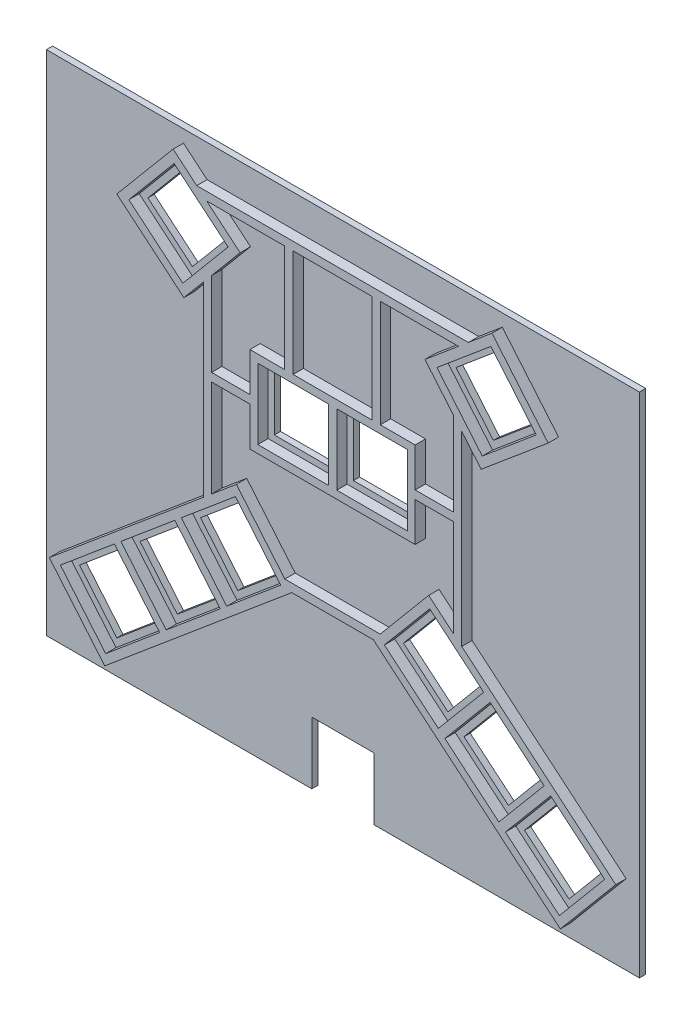
SolidWorks part; units mm, degrees
ref_plane "Alzado" through (0, 0, 0) normal (0, 0, 1) x (1, 0, 0)
ref_plane "Planta" through (0, 0, 0) normal (0, 1, 0) x (1, 0, 0)
ref_plane "Vista lateral" through (0, 0, 0) normal (1, 0, 0) x (0, 0, -1)
sketch "Model" plane through (0, 0, 0) normal (0, 0, 1) x (1, 0, 0)
  line L0 (0, 114.3975) -> (135.05, 114.3975)
  line L1 (135.05, 114.3975) -> (135.05, 0)
  line L2 (135.05, 0) -> (0, 0)
  line L3 (0, 0) -> (0, 114.3975)
  line L4 (51, 35) -> (65, 35)
  line L5 (65, 35) -> (65, 49)
  line L6 (65, 49) -> (51, 49)
  line L7 (51, 49) -> (51, 35)
  line L8 (67.525, 0) -> (67.525, 114.3975) construction
  line L9 (18.5931, 87.4278) -> (29.3178, 78.4288)
  line L10 (29.3178, 78.4288) -> (38.3168, 89.1534)
  line L11 (38.3168, 89.1534) -> (27.5922, 98.1524)
  line L12 (103.8144, 23.7236) -> (114.539, 14.7246)
  line L13 (94.8154, 12.999) -> (103.8144, 23.7236)
  line L14 (105.54, 4) -> (94.8154, 12.999)
  line L15 (114.539, 14.7246) -> (105.54, 4)
  line L16 (27.5922, 98.1524) -> (18.5931, 87.4278)
  line L17 (33.1863, 75.1827) -> (43.9109, 66.1836)
  line L18 (43.9109, 66.1836) -> (52.9099, 76.9083)
  line L19 (52.9099, 76.9083) -> (42.1853, 85.9073)
  line L20 (42.1853, 85.9073) -> (33.1863, 75.1827)
  line L21 (20.511, 14.7246) -> (29.51, 4)
  line L22 (29.51, 4) -> (40.2346, 12.999)
  line L23 (40.2346, 12.999) -> (31.2356, 23.7236)
  line L24 (31.2356, 23.7236) -> (20.511, 14.7246)
  line L25 (84.05, 49) -> (84.05, 35)
  line L26 (70.05, 49) -> (84.05, 49)
  line L27 (70.05, 35) -> (70.05, 49)
  line L28 (84.05, 35) -> (70.05, 35)
  line L29 (92.8647, 85.9073) -> (101.8637, 75.1827)
  line L30 (82.1401, 76.9083) -> (92.8647, 85.9073)
  line L31 (91.1391, 66.1836) -> (82.1401, 76.9083)
  line L32 (101.8637, 75.1827) -> (91.1391, 66.1836)
  line L33 (107.4578, 98.1524) -> (116.4569, 87.4278)
  line L34 (96.7332, 89.1534) -> (107.4578, 98.1524)
  line L35 (105.7322, 78.4288) -> (96.7332, 89.1534)
  line L36 (4, 99.6729) -> (14.7246, 90.6739)
  line L37 (14.7246, 90.6739) -> (23.7236, 101.3985)
  line L38 (23.7236, 101.3985) -> (12.999, 110.3975)
  line L39 (12.999, 110.3975) -> (4, 99.6729)
  line L40 (116.4569, 87.4278) -> (105.7322, 78.4288)
  line L41 (120.3254, 90.6739) -> (111.3264, 101.3985)
  line L42 (131.05, 99.6729) -> (120.3254, 90.6739)
  line L43 (122.051, 110.3975) -> (131.05, 99.6729)
  line L44 (4, 99.6729) -> (0, 99.6729) construction
  line L45 (111.3264, 101.3985) -> (122.051, 110.3975)
  line L46 (27.5922, 98.1524) -> (29.3178, 78.4288) construction
  line L47 (107.4578, 98.1524) -> (105.7322, 78.4288) construction
  line L48 (51, 35) -> (65, 49) construction
  line L49 (70.05, 49) -> (84.05, 35) construction
  line L50 (20.511, 14.7246) -> (40.2346, 12.999) construction
  line L51 (4, 99.6729) -> (0, 103.0293) construction
  line L52 (103.8144, 23.7236) -> (105.54, 4) construction
  line L54 (-4, 118.3975) -> (139.05, 118.3975)
  line L55 (-4, 118.3975) -> (-4, -4)
  line L56 (-4, -4) -> (139.05, -4)
  line L57 (139.05, 118.3975) -> (139.05, -4)
  line L58 (-4, 118.3975) -> (139.05, -4) construction
  line L59 (-4, -4) -> (139.05, 118.3975) construction
  point P8 (28.455, 88.2906)
  point P23 (106.595, 88.2906)
  point P50 (58, 42)
  point P51 (77.05, 42)
  point P52 (30.3728, 13.8618)
  point P54 (104.6772, 13.8618)
  point P55 (67.525, 57.1988)
  dimension "D1" = 14
  dimension "D8" = 4
  dimension "D2" = 4
  dimension "D3" = 40
  dimension "D4" = 114.3975
  dimension "D5" = 5.05
  dimension "D9" = 5.05
  dimension "D10" = 50
  dimension "D6" = 4
  dimension "D11" = 29.51
  dimension "D7" = 35
  dimension "D12" = 51
  dimension "D13" = 5.05
  dimension "D14" = 135.05
  dimension "D15" = 28.455
  dimension "D16" = 26.1069
  dimension "D17" = 106.595
  dimension "D18" = 26.1069
  dimension "D19" = 19.05
  dimension "D20" = 72.3975
  dimension "D21" = 67.525
  dimension "D22" = 100.5357
  dimension "D23" = 30.3728
  dimension "D24" = 104.6772
  dimension "D25" = 4
  dimension "D26" = 4
extrude "Saliente-Extruir1" add sketch "Model" along normal mid plane 1.5 contours L3 L2 L1 L0 L39 L38 L37 L36 L24 L23 L22 L21 L20 L19 L18 L17 L16 L11 L10 L9 L7 L6 L5 L4 L12 L15 L14 L13 L25 L28 L27 L26 L29 L32 L31 L30 L33 L40 L35 L34 L41 | L57 L54 L55 L56 L2 L3 L0 L1
sketch "Croquis1" plane through (0, 0, 0.75) normal (0, 0, 1) x (1, 0, 0)
  line L0 (-4, 118.3975) -> (-4, -4) construction
  line L2 (-4, 118.3975) -> (139.05, 118.3975) construction
  point P0 (12.5, 80.9213)
  dimension "D1" = 16.5
  dimension "D3" = 37.4762
sketch "Croquis2" plane through (0, 0, 0.75) normal (0, 0, 1) x (1, 0, 0)
  line L0 (-4, 118.3975) -> (139.05, 118.3975) construction
  line L1 (60.025, 133.3975) -> (75.025, 133.3975)
  line L2 (60.025, 133.3975) -> (60.025, 103.3975)
  line L3 (60.025, 103.3975) -> (75.025, 103.3975)
  line L4 (75.025, 133.3975) -> (75.025, 103.3975)
  line L5 (60.025, 133.3975) -> (75.025, 103.3975) construction
  line L6 (60.025, 103.3975) -> (75.025, 133.3975) construction
  point P0 (67.525, 118.3975)
  dimension "D1" = 15
  dimension "D2" = 15
extrude "Cortar-Extruir1" cut sketch "Croquis2" against normal through all
sketch "Croquis5" plane through (0, 0, -0.75) normal (0, 0, -1) x (-1, 0, 0)
  line L4 (-120.3254, 90.6739) -> (-111.3264, 101.3985)
  line L5 (-131.05, 99.6729) -> (-120.3254, 90.6739)
  line L6 (-122.051, 110.3975) -> (-131.05, 99.6729)
  line L7 (-111.3264, 101.3985) -> (-122.051, 110.3975)
  line L8 (-120.3254, 90.6739) -> (-111.3264, 101.3985)
  line L9 (-131.05, 99.6729) -> (-120.3254, 90.6739)
  line L10 (-122.051, 110.3975) -> (-131.05, 99.6729)
  line L11 (-111.3264, 101.3985) -> (-122.051, 110.3975)
  line L12 (-107.4578, 98.1524) -> (-116.4569, 87.4278)
  line L13 (-96.7332, 89.1534) -> (-107.4578, 98.1524)
  line L14 (-105.7322, 78.4288) -> (-96.7332, 89.1534)
  line L15 (-116.4569, 87.4278) -> (-105.7322, 78.4288)
  line L16 (-107.4578, 98.1524) -> (-116.4569, 87.4278)
  line L17 (-96.7332, 89.1534) -> (-107.4578, 98.1524)
  line L18 (-105.7322, 78.4288) -> (-96.7332, 89.1534)
  line L19 (-116.4569, 87.4278) -> (-105.7322, 78.4288)
  line L20 (-92.8647, 85.9073) -> (-101.8637, 75.1827)
  line L21 (-82.1401, 76.9083) -> (-92.8647, 85.9073)
  line L22 (-91.1391, 66.1836) -> (-82.1401, 76.9083)
  line L23 (-101.8637, 75.1827) -> (-91.1391, 66.1836)
  line L24 (-92.8647, 85.9073) -> (-101.8637, 75.1827)
  line L25 (-82.1401, 76.9083) -> (-92.8647, 85.9073)
  line L26 (-91.1391, 66.1836) -> (-82.1401, 76.9083)
  line L27 (-101.8637, 75.1827) -> (-91.1391, 66.1836)
  line L28 (-84.05, 49) -> (-84.05, 35)
  line L29 (-70.05, 49) -> (-84.05, 49)
  line L30 (-70.05, 35) -> (-70.05, 49)
  line L31 (-84.05, 35) -> (-70.05, 35)
  line L32 (-84.05, 49) -> (-84.05, 35)
  line L33 (-70.05, 49) -> (-84.05, 49)
  line L34 (-70.05, 35) -> (-70.05, 49)
  line L35 (-84.05, 35) -> (-70.05, 35)
  line L36 (-103.8144, 23.7236) -> (-114.539, 14.7246)
  line L37 (-94.8154, 12.999) -> (-103.8144, 23.7236)
  line L38 (-105.54, 4) -> (-94.8154, 12.999)
  line L39 (-114.539, 14.7246) -> (-105.54, 4)
  line L40 (-103.8144, 23.7236) -> (-114.539, 14.7246)
  line L41 (-94.8154, 12.999) -> (-103.8144, 23.7236)
  line L42 (-105.54, 4) -> (-94.8154, 12.999)
  line L43 (-114.539, 14.7246) -> (-105.54, 4)
  line L44 (-51, 35) -> (-51, 49)
  line L45 (-65, 35) -> (-51, 35)
  line L46 (-65, 49) -> (-65, 35)
  line L47 (-51, 49) -> (-65, 49)
  line L48 (-51, 35) -> (-51, 49)
  line L49 (-65, 35) -> (-51, 35)
  line L50 (-65, 49) -> (-65, 35)
  line L51 (-51, 49) -> (-65, 49)
  line L52 (-18.5931, 87.4278) -> (-27.5922, 98.1524)
  line L53 (-29.3178, 78.4288) -> (-18.5931, 87.4278)
  line L54 (-38.3168, 89.1534) -> (-29.3178, 78.4288)
  line L55 (-27.5922, 98.1524) -> (-38.3168, 89.1534)
  line L56 (-18.5931, 87.4278) -> (-27.5922, 98.1524)
  line L57 (-29.3178, 78.4288) -> (-18.5931, 87.4278)
  line L58 (-38.3168, 89.1534) -> (-29.3178, 78.4288)
  line L59 (-27.5922, 98.1524) -> (-38.3168, 89.1534)
  line L60 (-33.1863, 75.1827) -> (-42.1853, 85.9073)
  line L61 (-43.9109, 66.1836) -> (-33.1863, 75.1827)
  line L62 (-52.9099, 76.9083) -> (-43.9109, 66.1836)
  line L63 (-42.1853, 85.9073) -> (-52.9099, 76.9083)
  line L64 (-33.1863, 75.1827) -> (-42.1853, 85.9073)
  line L65 (-43.9109, 66.1836) -> (-33.1863, 75.1827)
  line L66 (-52.9099, 76.9083) -> (-43.9109, 66.1836)
  line L67 (-42.1853, 85.9073) -> (-52.9099, 76.9083)
  line L68 (-20.511, 14.7246) -> (-31.2356, 23.7236)
  line L69 (-29.51, 4) -> (-20.511, 14.7246)
  line L70 (-40.2346, 12.999) -> (-29.51, 4)
  line L71 (-31.2356, 23.7236) -> (-40.2346, 12.999)
  line L72 (-20.511, 14.7246) -> (-31.2356, 23.7236)
  line L73 (-29.51, 4) -> (-20.511, 14.7246)
  line L74 (-40.2346, 12.999) -> (-29.51, 4)
  line L75 (-31.2356, 23.7236) -> (-40.2346, 12.999)
  line L76 (-4, 99.6729) -> (-12.999, 110.3975)
  line L77 (-14.7246, 90.6739) -> (-4, 99.6729)
  line L78 (-23.7236, 101.3985) -> (-14.7246, 90.6739)
  line L79 (-12.999, 110.3975) -> (-23.7236, 101.3985)
  line L80 (-4, 99.6729) -> (-12.999, 110.3975)
  line L81 (-14.7246, 90.6739) -> (-4, 99.6729)
  line L82 (-23.7236, 101.3985) -> (-14.7246, 90.6739)
  line L83 (-12.999, 110.3975) -> (-23.7236, 101.3985)
  line L120 (-122.47, 115.1875) -> (-135.84, 99.2538)
  line L121 (-135.84, 99.2538) -> (-119.9063, 85.8838)
  line L123 (-106.5363, 101.8176) -> (-122.47, 115.1875)
  line L125 (-121.2469, 87.0087) -> (-105.3132, 73.6387)
  line L127 (-91.9432, 89.5724) -> (-107.8769, 102.9424)
  line L129 (-106.6537, 74.7636) -> (-98.6869, 68.0786)
  line L130 (-90.72, 61.3936) -> (-79.0282, 75.3273)
  line L131 (-77.35, 77.3273) -> (-93.2838, 90.6973)
  line L132 (-56.0218, 75.3273) -> (-44.33, 61.3936)
  line L133 (-44.33, 61.3936) -> (-38.3631, 66.4004)
  line L135 (-41.7662, 90.6973) -> (-57.7, 77.3273)
  line L137 (-29.7368, 73.6387) -> (-13.8031, 87.0087)
  line L139 (-27.1731, 102.9424) -> (-43.1068, 89.5724)
  line L141 (-15.1437, 85.8838) -> (0.79, 99.2538)
  line L142 (0.79, 99.2538) -> (-12.58, 115.1875)
  line L143 (-12.58, 115.1875) -> (-28.5137, 101.8176)
  line L144 (-87.45, 52.4) -> (-87.45, 43)
  line L145 (-87.45, 31.6) -> (-66.65, 31.6)
  line L147 (-66.65, 52.4) -> (-87.45, 52.4)
  line L149 (-68.4, 31.6) -> (-47.6, 31.6)
  line L150 (-47.6, 31.6) -> (-47.6, 41)
  line L151 (-47.6, 52.4) -> (-68.4, 52.4)
  line L160 (-107.8769, 102.9424) -> (-121.2469, 87.0087) construction
  line L161 (-119.9063, 85.8838) -> (-106.5363, 101.8176) construction
  line L162 (-93.2838, 90.6973) -> (-106.6537, 74.7636) construction
  line L163 (-105.3132, 73.6387) -> (-91.9432, 89.5724) construction
  line L164 (-43.1068, 89.5724) -> (-29.7368, 73.6387) construction
  line L165 (-28.3963, 74.7636) -> (-41.7662, 90.6973) construction
  line L166 (-28.5137, 101.8176) -> (-15.1437, 85.8838) construction
  line L167 (-13.8031, 87.0087) -> (-27.1731, 102.9424) construction
  line L168 (-68.4, 52.4) -> (-68.4, 31.6) construction
  line L169 (-66.65, 31.6) -> (-66.65, 52.4) construction
  line L170 (-103.3768, 28.725) -> (-119.5404, 15.1622)
  line L171 (-119.5404, 15.1622) -> (-105.9776, -1.0014)
  line L172 (-105.9776, -1.0014) -> (-89.814, 12.5615)
  line L173 (-89.814, 12.5615) -> (-96.6869, 20.7522)
  line L174 (-45.236, 12.5615) -> (-29.0724, -1.0014)
  line L175 (-29.0724, -1.0014) -> (-15.5096, 15.1622)
  line L176 (-15.5096, 15.1622) -> (-31.6732, 28.725)
  line L177 (-31.6732, 28.725) -> (-36.3631, 23.1357)
  line L178 (-122.2359, 112.5108) -> (-133.1632, 99.488)
  line L179 (-133.1632, 99.488) -> (-120.1405, 88.5606)
  line L180 (-120.1405, 88.5606) -> (-109.2131, 101.5834)
  line L181 (-109.2131, 101.5834) -> (-122.2359, 112.5108)
  line L182 (-107.6427, 100.2656) -> (-118.5701, 87.2429)
  line L183 (-118.5701, 87.2429) -> (-105.5473, 76.3155)
  line L184 (-105.5473, 76.3155) -> (-94.62, 89.3383)
  line L185 (-94.62, 89.3383) -> (-107.6427, 100.2656)
  line L186 (-93.0496, 88.0205) -> (-103.977, 74.9978)
  line L187 (-103.977, 74.9978) -> (-90.9542, 64.0704)
  line L188 (-90.9542, 64.0704) -> (-80.0268, 77.0932)
  line L189 (-80.0268, 77.0932) -> (-93.0496, 88.0205)
  line L190 (-55.0232, 77.0932) -> (-44.0958, 64.0704)
  line L191 (-44.0958, 64.0704) -> (-31.073, 74.9978)
  line L192 (-31.073, 74.9978) -> (-42.0004, 88.0205)
  line L193 (-42.0004, 88.0205) -> (-55.0232, 77.0932)
  line L194 (-40.43, 89.3383) -> (-29.5027, 76.3155)
  line L195 (-29.5027, 76.3155) -> (-16.4799, 87.2429)
  line L196 (-16.4799, 87.2429) -> (-27.4073, 100.2656)
  line L197 (-27.4073, 100.2656) -> (-40.43, 89.3383)
  line L198 (-25.8369, 101.5834) -> (-14.9095, 88.5606)
  line L199 (-14.9095, 88.5606) -> (-1.8868, 99.488)
  line L200 (-1.8868, 99.488) -> (-12.8141, 112.5108)
  line L201 (-12.8141, 112.5108) -> (-25.8369, 101.5834)
  line L202 (-85.55, 50.5) -> (-85.55, 33.5)
  line L203 (-85.55, 33.5) -> (-68.55, 33.5)
  line L204 (-68.55, 33.5) -> (-68.55, 50.5)
  line L205 (-68.55, 50.5) -> (-85.55, 50.5)
  line L206 (-66.5, 50.5) -> (-66.5, 33.5)
  line L207 (-66.5, 33.5) -> (-49.5, 33.5)
  line L208 (-49.5, 33.5) -> (-49.5, 50.5)
  line L209 (-49.5, 50.5) -> (-66.5, 50.5)
  line L210 (-103.6295, 25.8369) -> (-116.6523, 14.9095)
  line L211 (-116.6523, 14.9095) -> (-105.7249, 1.8868)
  line L212 (-105.7249, 1.8868) -> (-92.7021, 12.8141)
  line L213 (-92.7021, 12.8141) -> (-103.6295, 25.8369)
  line L214 (-31.4205, 25.8369) -> (-42.3479, 12.8141)
  line L215 (-42.3479, 12.8141) -> (-29.3251, 1.8868)
  line L216 (-29.3251, 1.8868) -> (-18.3977, 14.9095)
  line L217 (-18.3977, 14.9095) -> (-31.4205, 25.8369)
  line L218 (-67.525, 103.3975) -> (-67.525, -4) construction
  line L220 (-98.6869, 68.0786) -> (-98.6869, 23.1357)
  line L222 (-96.6869, 66.4004) -> (-96.6869, 43)
  line L223 (-60.025, 103.3975) -> (-75.025, 103.3975) construction
  line L224 (4, -4) -> (-139.05, -4) construction
  line L225 (-85.3169, 84.0123) -> (-98.6869, 68.0786) construction
  line L226 (-84.05, 42) -> (-100.0869, 42) construction
  line L227 (-96.6869, 41) -> (-87.45, 43) construction
  line L228 (-87.45, 43) -> (-96.6869, 43)
  line L230 (-87.45, 41) -> (-96.6869, 41)
  line L232 (-96.6869, 41) -> (-96.6869, 20.7522)
  line L234 (-36.3631, 68.0786) -> (-36.3631, 23.1357)
  line L236 (-38.3631, 41) -> (-38.3631, 20.7522)
  line L237 (-47.6, 41) -> (-38.3631, 41)
  line L239 (-47.6, 43) -> (-38.3631, 43)
  line L240 (-38.3631, 66.4004) -> (-38.3631, 43)
  line L241 (-96.6869, 66.4004) -> (-90.72, 61.3936)
  line L242 (-98.6869, 23.1357) -> (-103.3768, 28.725)
  line L243 (-106.6537, 74.7636) -> (-90.72, 61.3936) construction
  line L244 (-87.45, 41) -> (-87.45, 31.6)
  line L245 (-89.814, 12.5615) -> (-103.3768, 28.725) construction
  line L246 (-47.6, 43) -> (-47.6, 52.4)
  line L247 (-87.45, 52.4) -> (-87.45, 31.6) construction
  line L248 (-38.3631, 20.7522) -> (-45.236, 12.5615)
  line L249 (-47.6, 31.6) -> (-47.6, 52.4) construction
  line L250 (-36.3631, 68.0786) -> (-28.3963, 74.7636)
  line L251 (-31.6732, 28.725) -> (-45.236, 12.5615) construction
  line L252 (-77.35, 77.3273) -> (-57.7, 77.3273)
  line L253 (-44.33, 61.3936) -> (-28.3963, 74.7636) construction
  line L254 (-79.0282, 75.3273) -> (-56.0218, 75.3273)
  line L255 (-84.8741, 68.3605) -> (-84.8741, 52.4)
  line L256 (-90.72, 61.3936) -> (-77.35, 77.3273) construction
  line L257 (-57.7, 77.3273) -> (-44.33, 61.3936) construction
  line L258 (-82.8741, 70.744) -> (-82.8741, 52.4)
  line L259 (-50.1759, 68.3605) -> (-50.1759, 52.4)
  line L260 (-52.1759, 70.744) -> (-52.1759, 52.4)
  line L261 (-97.8958, 5.7801) -> (-37.1542, 5.7801)
  line L262 (-100.2793, 3.7801) -> (-34.7707, 3.7801)
  line L263 (-77.05, 31.6) -> (-77.05, 5.7801)
  line L264 (-58, 31.6) -> (-58, 5.7801)
  line L265 (-79.05, 31.6) -> (-79.05, 5.7801)
  line L266 (-56, 31.6) -> (-56, 5.7801)
  point P137 (-92.0684, 42)
  point P151 (-84.8741, 68.3605)
  dimension "D15" = 2
  dimension "D16" = 2
  dimension "D17" = 2
  dimension "D18" = 2
  dimension "D19" = 2
  dimension "D20" = 2
  dimension "D21" = 2
  dimension "D22" = 2
  dimension "D1" = 0
  dimension "D2" = 0
  dimension "D3" = 0
  dimension "D4" = 0
  dimension "D5" = 0
  dimension "D6" = 0
  dimension "D7" = 0
  dimension "D8" = 0
  dimension "D9" = 0
  dimension "D10" = 0
  dimension "D11" = 3.4
  dimension "D12" = 3.55
  dimension "D13" = 1.5
  dimension "D14" = 1.5
extrude "Saliente-Extruir2" add sketch "Croquis5" along normal blind 2.5 contours L176 L177 L174 L175 L217 L216 L215 L214 | L172 L262 L174 L261 | L145 L265 L261 L263 | L266 L149 L264 L261
move or copy body "Sólido-Mover/Copiar1" bodies to move or copy 103 copy no rotation origin (0, 57.1988, -0.75) rotation axis (1, 0, 0) rotation angle 180
equation "\"G\"= 4"
equation "\"D26@Model\"=\"G\""
equation "\"D25@Model\"=\"G\""
